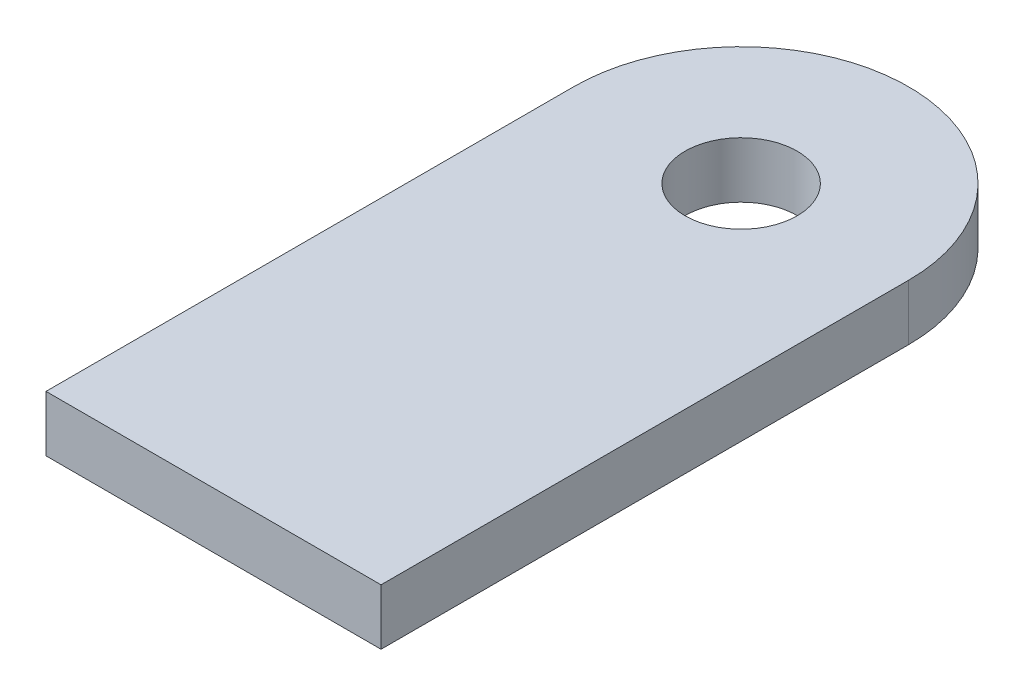
SolidWorks part; units mm, degrees
ref_plane "Front Plane" through (0, 0, 0) normal (0, 0, 1) x (1, 0, 0)
ref_plane "Top Plane" through (0, 0, 0) normal (0, 1, 0) x (1, 0, 0)
ref_plane "Right Plane" through (0, 0, 0) normal (1, 0, 0) x (0, 0, -1)
sketch "Sketch1" plane through (0, 0, 0) normal (0, 1, 0) x (1, 0, 0)
  line L1 (0, 0) -> (25.4, 0)
  line L2 (0, 0) -> (0, 40)
  line L3 (0, 40) -> (25.4, 40)
  line L4 (25.4, 0) -> (25.4, 40)
  arc A0 (0, 40) -> (25.4, 40) centre (12.7, 40) cw
  circle A1 centre (12.7, 40) radius 4.25
  dimension "D1" = 8.5
  dimension "D2" = 25.4
  dimension "D3" = 40
extrude "Boss-Extrude1" add sketch "Sketch1" along normal blind 4.2333 contours A1 L3 L2 L1 L4 | A1 L3 A0
